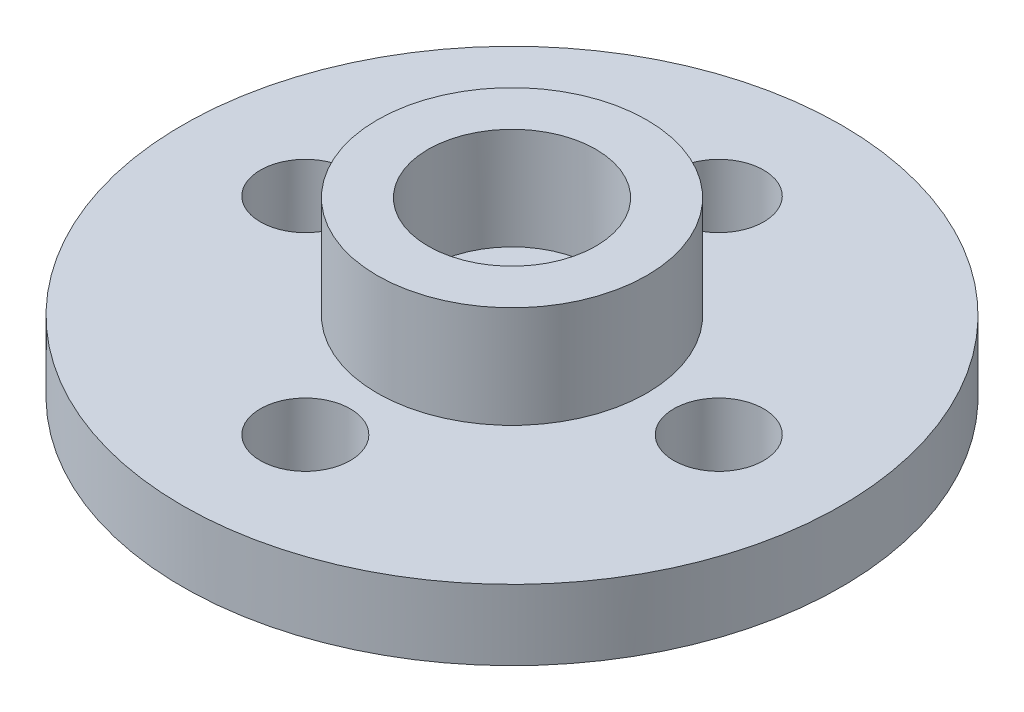
SolidWorks part; units mm, degrees
ref_plane "Front Plane" through (0, 0, 0) normal (0, 0, 1) x (1, 0, 0)
ref_plane "Top Plane" through (0, 0, 0) normal (0, 1, 0) x (1, 0, 0)
ref_plane "Right Plane" through (0, 0, 0) normal (1, 0, 0) x (0, 0, -1)
sketch "Sketch1" plane through (0, 0, 0) normal (0, 1, 0) x (1, 0, 0)
  circle A0 centre (0, 0) radius 11
  dimension "10" = 22
extrude "Boss-Extrude2" add sketch "Sketch1" along normal blind 5.65
sketch "Sketch3" plane through (0, 5.65, 0) normal (0, 1, 0) x (1, 0, 0)
  line L0 (-2.8, 0) -> (-11, 0) construction
  line L1 (0, 2.8) -> (0, 11) construction
  line L2 (0, -2.8) -> (0, -11) construction
  line L3 (2.8, 0) -> (11, 0) construction
  circle A0 centre (0, 0) radius 2.8
  circle A1 centre (0, 0) radius 11 construction
  circle A2 centre (-6.9, 0) radius 1.5
  circle A3 centre (0, 6.9) radius 1.5
  circle A4 centre (6.9, 0) radius 1.5
  circle A5 centre (0, -6.9) radius 1.5
  dimension "D1" = 5.6
  dimension "D2" = 3
  dimension "D3" = 3
  dimension "D4" = 3
  dimension "D5" = 3
extrude "Cut-Extrude2" cut sketch "Sketch3" against normal blind 12
sketch "Sketch4" plane through (0, 5.65, 0) normal (0, 1, 0) x (1, 0, 0)
  circle A0 centre (0, 0) radius 4.5
  circle A1 centre (0, 0) radius 11
  dimension "D1" = 9
extrude "Cut-Extrude3" cut sketch "Sketch4" against normal blind 4
ref_plane "Plane1" through (10, 0, 0) normal (1, 0, 0) x (0, 0, -1)
sketch "Sketch5" plane through (10, 0, 0) normal (1, 0, 0) x (0, 0, -1)
  line L0 (0, 1.65) -> (0, 5.05) construction
  line L1 (11, 1.65) -> (-11, 1.65) construction
  line L2 (4.5, 1.65) -> (4.5, 5.65) construction
  line L3 (-4.5, 5.65) -> (4.5, 5.65)
  line L4 (-4.5, 5.65) -> (-4.5, 5.05)
  line L5 (-4.5, 5.05) -> (4.5, 5.05)
  line L6 (4.5, 5.65) -> (4.5, 5.05)
extrude "Cut-Extrude4" cut sketch "Sketch5" against normal blind 18
sketch "Sketch6" plane through (0, 1.65, 0) normal (0, 1, 0) x (1, 0, 0)
  circle A0 centre (0, 0) radius 2.8
  circle A1 centre (0, 0) radius 1.5
  dimension "3" = 3
extrude "Boss-Extrude4" add sketch "Sketch6" against normal blind 2.3
sketch "Sketch7" plane through (0, 0, 0) normal (0, -1, 0) x (1, 0, 0)
  circle A0 centre (0, 0) radius 2.8
  circle A1 centre (0, 0) radius 11
  circle A2 centre (0, 6.9) radius 1.5
  circle A3 centre (6.9, 0) radius 1.5
  circle A4 centre (0, -6.9) radius 1.5
  circle A5 centre (-6.9, 0) radius 1.5
extrude "Boss-Extrude5" add sketch "Sketch7" along normal blind 0.7
